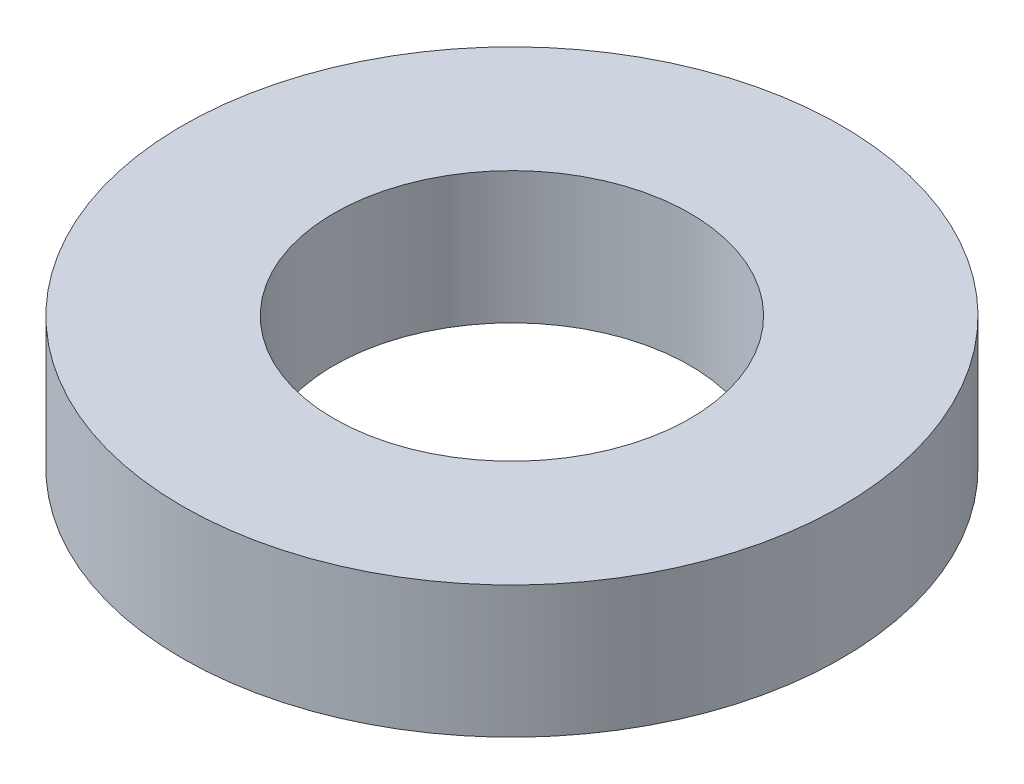
SolidWorks part; units mm, degrees
ref_plane "Front Plane" through (0, 0, 0) normal (0, 0, 1) x (1, 0, 0)
ref_plane "Top Plane" through (0, 0, 0) normal (0, 1, 0) x (1, 0, 0)
ref_plane "Right Plane" through (0, 0, 0) normal (1, 0, 0) x (0, 0, -1)
sketch "Sketch1" plane through (0, 0, 0) normal (0, 1, 0) x (1, 0, 0)
  circle A0 centre (0, 0) radius 2.7
  circle A1 centre (0, 0) radius 5
  dimension "D1" = 5.4
  dimension "D2" = 10
extrude "Boss-Extrude1" add sketch "Sketch1" along normal blind 2
